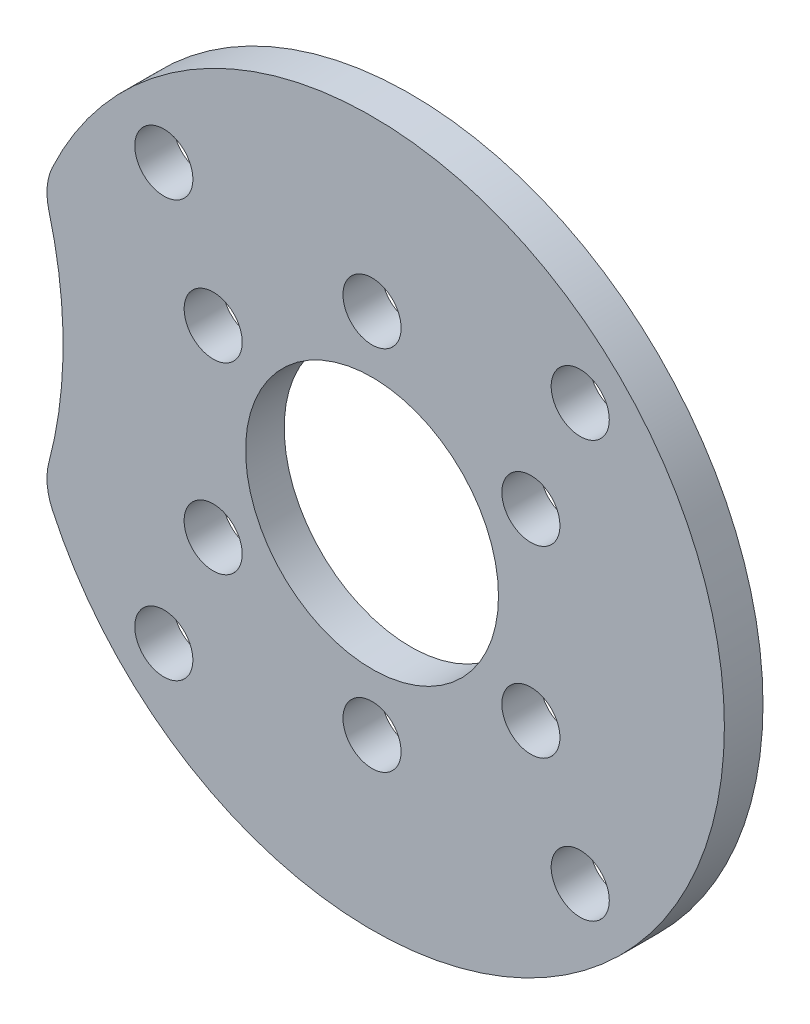
SolidWorks part; units mm, degrees
material "Thornel Mat VMA"
ref_plane "前视基准面" through (0, 0, 0) normal (0, 0, 1) x (1, 0, 0)
ref_plane "上视基准面" through (0, 0, 0) normal (0, 1, 0) x (1, 0, 0)
ref_plane "右视基准面" through (0, 0, 0) normal (1, 0, 0) x (0, 0, -1)
sketch "草图1" plane through (0, 0, 0) normal (0, 0, 1) x (1, 0, 0)
  circle A0 centre (0, 0) radius 6.55
  circle A1 centre (0, 0) radius 18.25
  dimension "D1" = 13.1
  dimension "D2" = 36.5
extrude "凸台-拉伸1" add sketch "草图1" along normal blind 2
sketch "草图2" plane through (0, 0, 2) normal (0, 0, 1) x (1, 0, 0)
  circle A0 centre (-38, 0) radius 22
  dimension "D2" = 44
  dimension "D1" = 38
extrude "切除-拉伸1" cut sketch "草图2" against normal blind 2
sketch "草图3" plane through (0, 0, 2) normal (0, 0, 1) x (1, 0, 0)
  line L0 (0, 9.5) -> (0, 0) construction
  line L1 (0, 0) -> (8.2272, -4.75) construction
  line L2 (0, 0) -> (-8.2272, -4.75) construction
  circle A0 centre (0, 0) radius 9.5 construction
  circle A1 centre (0, 9.5) radius 1.505
  circle A2 centre (8.2272, -4.75) radius 1.505
  circle A3 centre (-8.2272, -4.75) radius 1.505
  dimension "D1" = 19
  dimension "D4" = 3.01
  dimension "D2" = 120
  dimension "D3" = 120
extrude "切除-拉伸2" cut sketch "草图3" against normal blind 2
pattern_circular "阵列(圆周)1" count 2 over 360 about axis through (0, 0, 0) along (0, 0, 1) of "切除-拉伸2"
sketch "草图4" plane through (0, 0, 2) normal (0, 0, 1) x (1, 0, 0)
  line L0 (-10.7834, 10.7834) -> (0, 0) construction
  line L1 (0, 0) -> (0, 15.25) construction
  circle A1 centre (-10.7834, 10.7834) radius 1.505
  arc A2 (-14.2172, -5.5168) -> (-14.2172, 5.5168) centre (0, 0) ccw
  arc A3 (-14.2172, -5.5168) -> (-14.2172, 5.5168) centre (0, 0) ccw construction
  circle A4 centre (10.7834, 10.7834) radius 1.505
  circle A5 centre (10.7834, -10.7834) radius 1.505
  circle A6 centre (-10.7834, -10.7834) radius 1.505
  point P15 (0, 0)
  dimension "D3" = 3.01
  dimension "D2" = 45
  dimension "D1" = 3
  dimension "D4" = 4
extrude "切除-拉伸3" cut sketch "草图4" against normal blind 2
fillet "圆角1" radius 3 2 edges at (-17.014, 6.602, 1) (-17.014, -6.602, 1)
